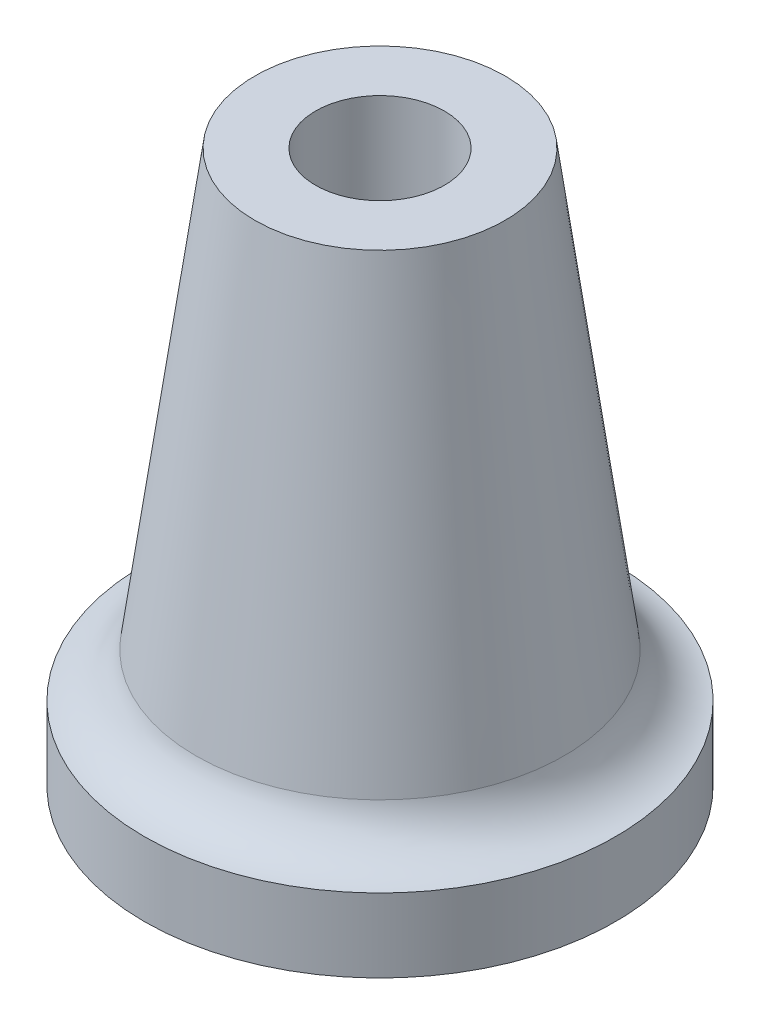
SolidWorks part; units mm, degrees
ref_plane "Plan de face" through (0, 0, 0) normal (0, 0, 1) x (1, 0, 0)
ref_plane "Plan de dessus" through (0, 0, 0) normal (0, 1, 0) x (1, 0, 0)
ref_plane "Plan de droite" through (0, 0, 0) normal (1, 0, 0) x (0, 0, -1)
sketch "Esquisse1" plane through (0, 0, 0) normal (0, 0, 1) x (1, 0, 0)
  line L0 (0, -112.3795) -> (0, 933.4876) construction
  line L1 (0, -79.0212) -> (320, -79.0212)
  line L2 (320, -79.0212) -> (320, 20.9788)
  line L3 (320, 20.9788) -> (0, 20.9788)
  line L4 (0, 20.9788) -> (0, -79.0212)
  line L5 (0, 80.9788) -> (250, 80.9788)
  line L6 (0, 80.9788) -> (0, 20.9788)
  line L7 (0, 80.9788) -> (0, 670.9788)
  line L8 (0, 670.9788) -> (170, 670.9788)
  line L9 (170, 670.9788) -> (250, 80.9788)
  line L10 (180, -79.0212) -> (180, -39.0212)
  line L11 (180, -39.0212) -> (0, -39.0212)
  line L12 (115, -39.0212) -> (115, 290.9788)
  line L13 (115, 290.9788) -> (0, 290.9788)
  line L14 (87.5, 290.9788) -> (87.5, 670.9788)
  arc A0 (250, 80.9788) -> (320, 20.9788) centre (327.551, 100.6217) ccw
  dimension "D6" = 160
  dimension "D1" = 112.3795
  dimension "D2" = 320
  dimension "D3" = 100
  dimension "D4" = 79.0212
  dimension "D5" = 250
  dimension "D7" = 60
  dimension "D8" = 750
  dimension "D9" = 170
  dimension "D10" = 180
  dimension "D11" = 87.5
  dimension "D12" = 115
  dimension "D13" = 330
  dimension "D14" = 40
revolve "Révolution1" add sketch "Esquisse1" angle 360 about L0
